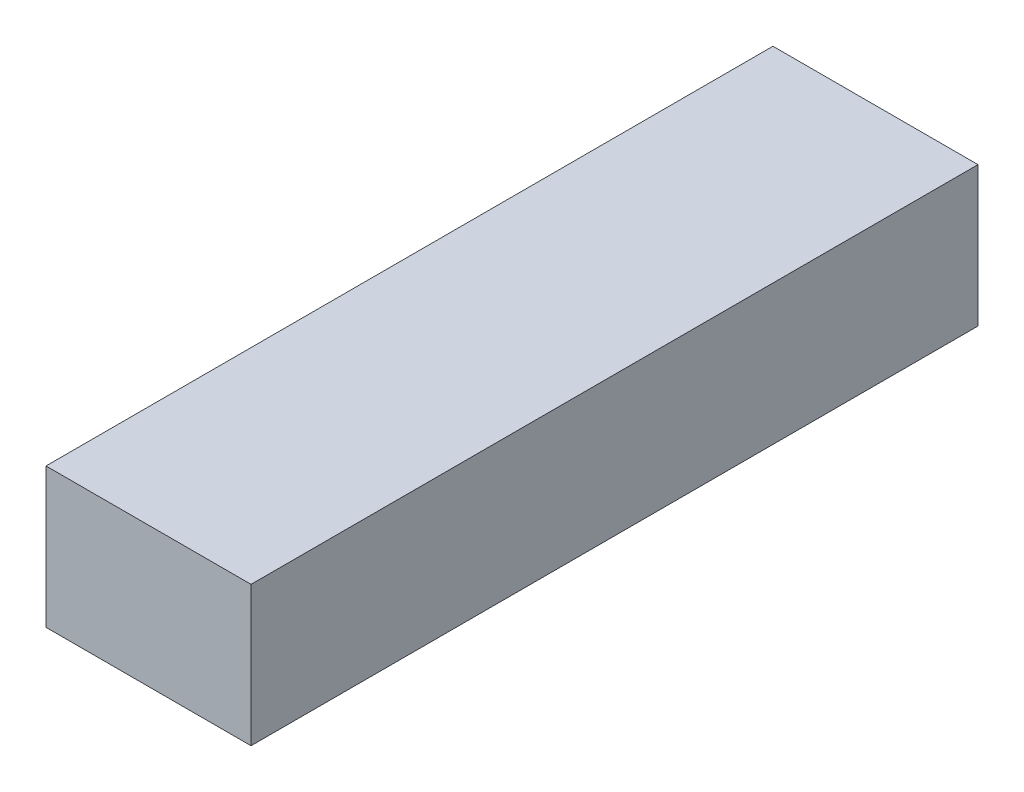
SolidWorks part; units mm, degrees
ref_plane "Front Plane" through (0, 0, 0) normal (0, 0, 1) x (1, 0, 0)
ref_plane "Top Plane" through (0, 0, 0) normal (0, 1, 0) x (1, 0, 0)
ref_plane "Right Plane" through (0, 0, 0) normal (1, 0, 0) x (0, 0, -1)
sketch "Sketch1" plane through (0, 0, 0) normal (0, 1, 0) x (1, 0, 0)
  line L0 (-1, -1) -> (-1, 30.2)
  line L1 (0, 0) -> (6.8, 0)
  line L2 (0, 0) -> (0, 29.2)
  line L3 (0, 29.2) -> (6.8, 29.2)
  line L4 (6.8, 0) -> (6.8, 29.2)
  line L5 (-1, 30.2) -> (7.8, 30.2)
  line L6 (7.8, -1) -> (7.8, 30.2)
  line L7 (-1, -1) -> (7.8, -1)
  dimension "D1" = 29.2
  dimension "D2" = 6.8
  dimension "D3" = 1
extrude "Boss-Extrude1" add sketch "Sketch1" along normal blind 5
sketch "Sketch2" plane through (0, 5, 0) normal (0, 1, 0) x (1, 0, 0)
  line L1 (7.8, 30.2) -> (-1, 30.2)
  line L2 (7.8, 30.2) -> (7.8, -1)
  line L3 (7.8, -1) -> (-1, -1)
  line L4 (-1, 30.2) -> (-1, -1)
extrude "Boss-Extrude2" add sketch "Sketch2" along normal blind 1
sketch "Sketch3" plane through (-1, 0, 0) normal (-1, 0, 0) x (0, 0, 1)
  line L1 (-29.2, 0) -> (0, 0)
  line L2 (-29.2, 0) -> (-29.2, 2)
  line L3 (-29.2, 2) -> (0, 2)
  line L4 (0, 0) -> (0, 2)
  line L5 (-29.2, 0) -> (0, 2) construction
  line L6 (-29.2, 2) -> (0, 0) construction
  point P4 (-14.6, 1)
  dimension "D1" = 2
extrude "Cut-Extrude1" cut sketch "Sketch3" against normal up to next
